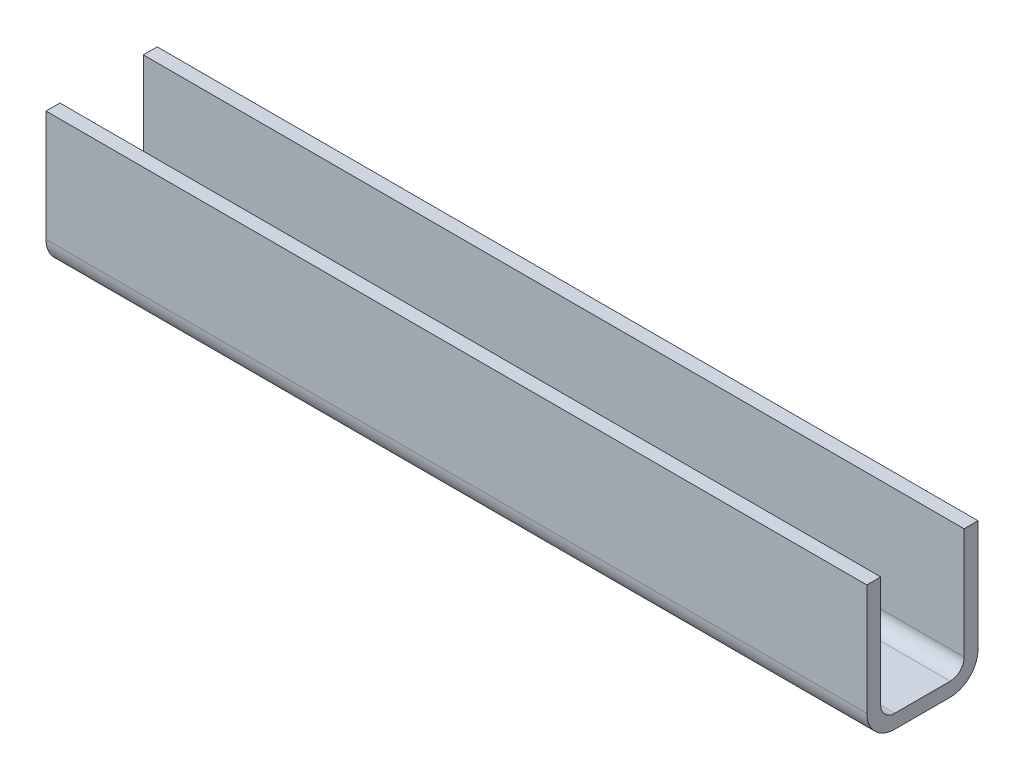
SolidWorks part; units mm, degrees
ref_plane "Alzado" through (0, 0, 0) normal (0, 0, 1) x (1, 0, 0)
ref_plane "Planta" through (0, 0, 0) normal (0, 1, 0) x (1, 0, 0)
ref_plane "Vista lateral" through (0, 0, 0) normal (1, 0, 0) x (0, 0, -1)
sketch "Croquis1" plane through (0, 0, 0) normal (0, 1, 0) x (1, 0, 0)
  line L0 (0, 0) -> (375, 0)
  dimension "D1" = 375
other "Tubo rectangular 3 X 2 X 0.25(1)"
ref_plane "Plano1" through (0, 0, 0) normal (1, 0, 0) x (0, 0, -1)
sketch "Sketch1" plane through (0, 0, 0) normal (1, 0, 0) x (0, 0, -1)
  line L0 (-12.7, -31.75) -> (12.7, -31.75)
  line L1 (-19.05, -25.4) -> (-19.05, 25.4)
  line L2 (12.7, 31.75) -> (-12.7, 31.75)
  line L3 (19.05, 25.4) -> (19.05, -25.4)
  line L4 (-12.7, -38.1) -> (12.7, -38.1)
  line L5 (-25.4, -25.4) -> (-25.4, 25.4)
  line L6 (12.7, 38.1) -> (-12.7, 38.1)
  line L7 (25.4, 25.4) -> (25.4, -25.4)
  line L8 (0, 0) -> (25.4, 0) construction
  line L9 (0, 0) -> (0, 38.1) construction
  arc A0 (25.4, 25.4) -> (12.7, 38.1) centre (12.7, 25.4) ccw
  arc A1 (12.7, -38.1) -> (25.4, -25.4) centre (12.7, -25.4) ccw
  arc A2 (-25.4, -25.4) -> (-12.7, -38.1) centre (-12.7, -25.4) ccw
  arc A3 (-12.7, 38.1) -> (-25.4, 25.4) centre (-12.7, 25.4) ccw
  arc A4 (-12.7, 31.75) -> (-19.05, 25.4) centre (-12.7, 25.4) ccw
  arc A5 (19.05, 25.4) -> (12.7, 31.75) centre (12.7, 25.4) ccw
  arc A6 (12.7, -31.75) -> (19.05, -25.4) centre (12.7, -25.4) ccw
  arc A7 (-19.05, -25.4) -> (-12.7, -31.75) centre (-12.7, -25.4) ccw
  point P3 (0, -38.1)
  point P4 (-25.4, 0)
  point P5 (0, 0)
  point P6 (25.4, -38.1)
  point P7 (-25.4, -38.1)
  point P8 (-25.4, 38.1)
  point P33 (0, 0)
  point P35 (25.4, 38.1)
  point P36 (25.4, 0)
  point P37 (0, 38.1)
  dimension "D1" = 12.7
  dimension "Thickness" = 6.35
  dimension "V_leg" = 76.2
  dimension "H_leg" = 50.8
sketch "Croquis3" plane through (0, 0, -25.4) normal (0, 0, -1) x (-1, 0, 0)
  line L0 (-375, -38.1) -> (-375, 25.4) construction
  line L1 (-375, 25.4) -> (0, 25.4)
  line L2 (0, 25.4) -> (0, 38.1) construction
  line L3 (0, -25.4) -> (0, 25.4) construction
  line L4 (0, 25.4) -> (0, 38.1)
  line L5 (0, 38.1) -> (-375, 38.1)
  line L6 (-375, 38.1) -> (-375, 25.4)
  dimension "D1" = 63.5
extrude "Cortar-Extruir1" cut sketch "Croquis3" against normal blind 78
